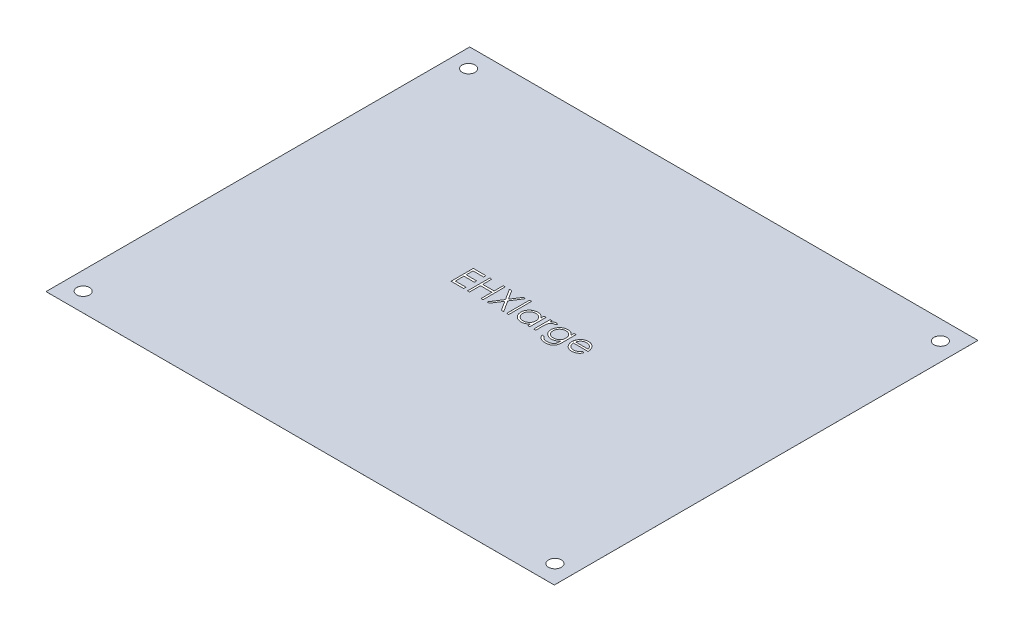
SolidWorks part; units mm, degrees
ref_plane "Front Plane" through (0, 0, 0) normal (0, 0, 1) x (1, 0, 0)
ref_plane "Top Plane" through (0, 0, 0) normal (0, 1, 0) x (1, 0, 0)
ref_plane "Right Plane" through (0, 0, 0) normal (1, 0, 0) x (0, 0, -1)
sketch "Sketch2" plane through (0, 0, 0) normal (0, 1, 0) x (1, 0, 0)
  line L1 (-72.517, -60.452) -> (72.517, -60.452)
  line L2 (-72.517, -60.452) -> (-72.517, 60.452)
  line L3 (-72.517, 60.452) -> (72.517, 60.452)
  line L4 (72.517, -60.452) -> (72.517, 60.452)
  line L5 (-72.517, -60.452) -> (72.517, 60.452) construction
  line L6 (-72.517, 60.452) -> (72.517, -60.452) construction
  point P0 (0, 0)
  dimension "D1" = 120.904
  dimension "D2" = 145.034
extrude "Boss-Extrude1" add sketch "Sketch2" along normal blind 0.0025
sketch "Sketch3" plane through (0, 0.0025, 0) normal (0, 1, 0) x (1, 0, 0)
  line L1 (-67.31, -54.9275) -> (67.31, -54.9275)
  line L2 (-67.31, -54.9275) -> (-67.31, 54.9275)
  line L3 (-67.31, 54.9275) -> (67.31, 54.9275)
  line L4 (67.31, -54.9275) -> (67.31, 54.9275)
  line L5 (-67.31, -54.9275) -> (67.31, 54.9275) construction
  line L6 (-67.31, 54.9275) -> (67.31, -54.9275) construction
  circle A0 centre (-67.31, 54.9275) radius 1.8288
  circle A7 centre (67.31, 54.9275) radius 1.8288
  circle A8 centre (67.31, -55.0545) radius 1.8288
  circle A9 centre (-67.31, -55.0545) radius 1.8288
  point P0 (0, 0)
  dimension "D3" = 3.6576
  dimension "D1" = 109.855
  dimension "D2" = 134.62
  dimension "D4" = 2
  dimension "D5" = 2
extrude "Cut-Extrude1" cut sketch "Sketch3" against normal through all contours A9 | A8 | A7 | A0
sketch "Sketch5" plane through (0, 0.0025, 0) normal (0, 1, 0) x (1, 0, 0)
  text T0 "EHXlarge\r\n" font "Century Gothic" height 6.35
extrude "Cut-Extrude2" cut sketch "Sketch5" against normal blind 2.54
